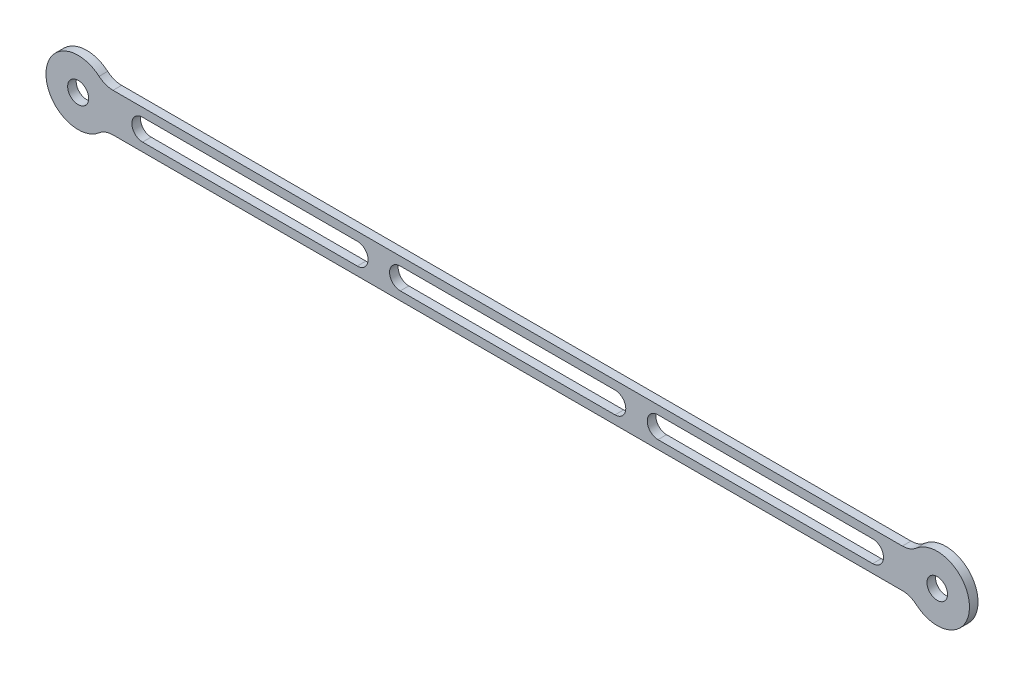
SolidWorks part; units mm, degrees
ref_plane "Front Plane" through (0, 0, 0) normal (0, 0, 1) x (1, 0, 0)
ref_plane "Top Plane" through (0, 0, 0) normal (0, 1, 0) x (1, 0, 0)
ref_plane "Right Plane" through (0, 0, 0) normal (1, 0, 0) x (0, 0, -1)
sketch "Sketch1" plane through (0, 0, 0) normal (0, 0, 1) x (1, 0, 0)
  line L0 (6, 0) -> (194.02, 0) construction
  line L1 (6, 4.5) -> (194.02, 4.5)
  line L2 (6, 4.5) -> (6, -4.5)
  line L3 (6, -4.5) -> (194.02, -4.5)
  line L4 (194.02, 4.5) -> (194.02, -4.5)
  line L5 (200.02, 0) -> (197.62, 0) construction
  line L6 (0, 0) -> (2.45, 0) construction
  circle A0 centre (0, 0) radius 2.45
  circle A1 centre (0, 0) radius 7.5
  circle A2 centre (200.02, 0) radius 2.4
  circle A3 centre (200.02, 0) radius 7.5
  dimension "D1" = 200.02
  dimension "D2" = 4.9
  dimension "D3" = 15
  dimension "D5" = 4.8
  dimension "D4" = 9
extrude "Boss-Extrude1" add sketch "Sketch1" along normal blind 2 contours A3 L1 A1 L3 | L4 A3 | L4 A3 A2 | L2 A1 L3 A0 | L3 A1 L2
sketch "Sketch2" plane through (0, 0, 2) normal (0, 0, 1) x (1, 0, 0)
  line L0 (75, 0) -> (125, 0) construction
  line L1 (75, 2.5) -> (125, 2.5)
  line L2 (75, -2.5) -> (125, -2.5)
  line L3 (135, 0) -> (185, 0) construction
  line L4 (135, 2.5) -> (185, 2.5)
  line L5 (135, -2.5) -> (185, -2.5)
  line L6 (15, 0) -> (65, 0) construction
  line L7 (15, 2.5) -> (65, 2.5)
  line L8 (15, -2.5) -> (65, -2.5)
  arc A0 (75, 2.5) -> (75, -2.5) centre (75, 0) ccw
  arc A1 (125, -2.5) -> (125, 2.5) centre (125, 0) ccw
  arc A2 (135, 2.5) -> (135, -2.5) centre (135, 0) ccw
  arc A3 (185, -2.5) -> (185, 2.5) centre (185, 0) ccw
  arc A4 (15, 2.5) -> (15, -2.5) centre (15, 0) ccw
  arc A5 (65, -2.5) -> (65, 2.5) centre (65, 0) ccw
  point P3 (100, 0)
  point P12 (160, 0)
  point P18 (40, 0)
  dimension "D1" = 50
  dimension "D2" = 100
  dimension "D3" = 5
  dimension "D4" = 2
  dimension "D5" = 2
extrude "Cut-Extrude1" cut sketch "Sketch2" against normal through all
fillet "Fillet1" radius 5 4 edges at (194.02, 4.5, 1) (194.02, -4.5, 1) (6, -4.5, 1) (6, 4.5, 1)
